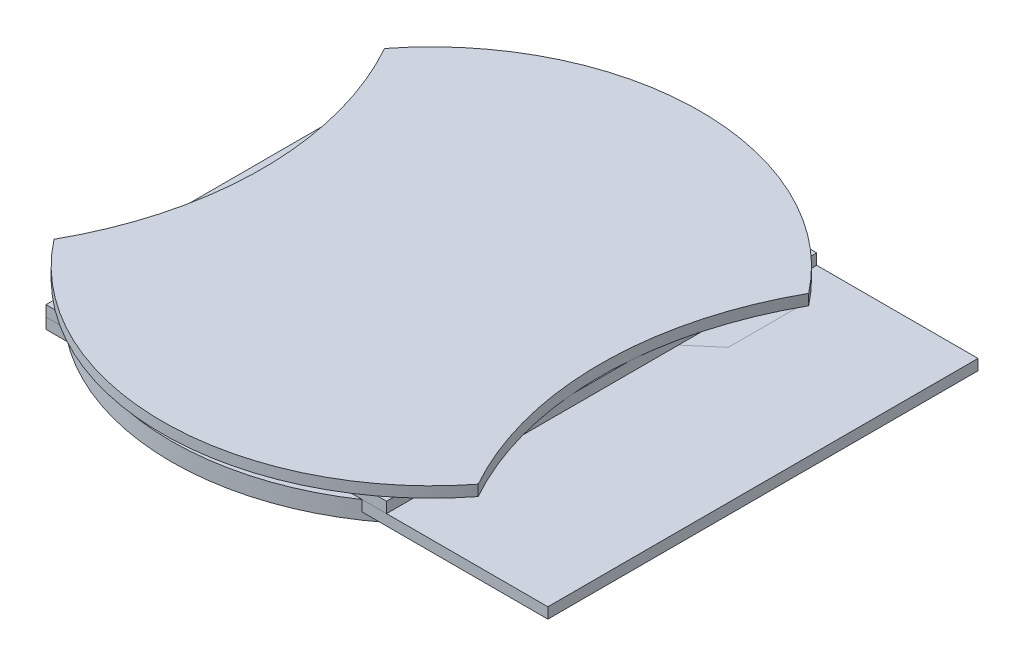
SolidWorks part; units mm, degrees
other "Markup1"
sketch "Sketch33" plane through (-11.66, 9, -138.7946) normal (0, 1, 0) x (1, 0, 0)
other "Markup2"
sketch "Sketch43" plane through (-27.5, 9, 15) normal (-0.0208, 0.9953, 0.0943) x (0.8809, -0.0263, 0.4725)
other "Markup3"
sketch "Sketch50" plane through (-27.5, -2, -135) normal (0, -1, 0) x (1, 0, 0)
material "PMMA"
ref_plane "Front Plane" through (0, 0, 0) normal (0, 0, 1) x (1, 0, 0)
ref_plane "Top Plane" through (0, 0, 0) normal (0, 1, 0) x (1, 0, 0)
ref_plane "Right Plane" through (0, 0, 0) normal (1, 0, 0) x (0, 0, -1)
sketch "Sketch1" plane through (0, 0, 0) normal (0, 1, 0) x (1, 0, 0)
  line L1 (0, 0) -> (140, 0)
  line L2 (0, 0) -> (0, 120)
  line L3 (0, 120) -> (140, 120)
  line L4 (140, 0) -> (140, 120)
  dimension "D1" = 120
  dimension "D2" = 140
extrude "Compact" add sketch "Sketch1" along normal blind 3
sketch "Center Guide" plane through (0, 0, 0) normal (-1, 0, 0) x (0, 0, 1)
  line L0 (-60, 0) -> (-60, -3) construction
  line L1 (-120, 0) -> (0, 0) construction
  line L2 (-60, 3) -> (-60, 16.3)
  line L3 (-120, 3) -> (0, 3) construction
  line L4 (-60, 3) -> (-60, 24.5)
  circle A0 centre (-60, -3) radius 10.0584
  circle A1 centre (-60, 16.3) radius 5.9898
  circle A2 centre (-60, 24.5) radius 8.3651
  dimension "D2" = 13.3
  dimension "D3" = 21.5
  dimension "D1" = 3
sketch "Sketch4" plane through (0, 3, 0) normal (0, 1, 0) x (1, 0, 0)
  line L0 (0, 0) -> (140, 0) construction
  line L1 (0, 120) -> (95, 120)
  line L2 (0, 120) -> (0, 0)
  line L3 (0, 0) -> (95, 0)
  line L4 (95, 120) -> (95, 0)
  dimension "D1" = 95
extrude "SuperCompact" add sketch "Sketch4" along normal blind 3 separate body
sketch "Sketch5" plane through (0, 6, 0) normal (0, 1, 0) x (1, 0, 0)
  line L0 (47.5, 120) -> (47.5, 103.0921) construction
  line L1 (95, 120) -> (0, 120) construction
  line L2 (0, 60) -> (21.8037, 60) construction
  line L3 (0, 120) -> (0, 0) construction
  line L4 (70, 120) -> (70, 93.0513) construction
  line L5 (140, 120) -> (0, 120) construction
  circle A0 centre (5, 115) radius 1.5
  circle A1 centre (90, 115) radius 1.5
  circle A2 centre (90, 5) radius 1.5
  circle A3 centre (5, 5) radius 1.5
  circle A4 centre (135, 5) radius 1.5
  circle A5 centre (135, 115) radius 1.5
  dimension "D1" = 3
  dimension "D2" = 5
  dimension "D3" = 5
sketch "Sketch7" plane through (0, 6, 0) normal (0, 1, 0) x (1, 0, 0)
  line L0 (47.5, 120) -> (47.5, 0) construction
  line L1 (95, 120) -> (0, 120) construction
  line L2 (0, 0) -> (95, 0) construction
  circle A0 centre (47.5, 60) radius 75
  dimension "D1" = 150
extrude "Apple Base" add sketch "Sketch7" along normal blind 3 separate body
sketch "Sketch8" plane through (0, 9, 0) normal (0, 1, 0) x (1, 0, 0)
  line L1 (0, 120) -> (0, 0) construction
  line L2 (0, 100.6202) -> (0, 77.7186) construction
  line L3 (47.5, 135) -> (47.5, 108.0988) construction
  line L7 (-27.5, 60) -> (-27.5, 91.6393) construction
  arc A1 (-11.66, 106.0987) -> (-11.66, 13.9013) centre (-94.1268, 60) cw
  circle A2 centre (47.5, 60) radius 75 construction
  circle A3 centre (47.5, 60) radius 75
  arc A4 (-11.66, 106.0987) -> (-11.66, 13.9013) centre (47.5, 60) ccw
  arc A5 (106.66, 106.0987) -> (106.66, 13.9013) centre (189.1268, 60) ccw
  arc A6 (106.66, 106.0987) -> (106.66, 13.9013) centre (47.5, 60) cw
  dimension "D2" = 0
extrude "SideCuts" cut sketch "Sketch8" against normal through all
sketch "Sketch9" plane through (0, 6, 0) normal (0, -1, 0) x (1, 0, 0)
  arc A4 (106.66, -13.9013) -> (-11.66, -13.9013) centre (47.5, -60) ccw
  arc A5 (-11.66, -106.0987) -> (-11.66, -13.9013) centre (-94.1268, -60) ccw
  arc A6 (-11.66, -106.0987) -> (106.66, -106.0987) centre (47.5, -60) ccw
  arc A7 (106.66, -13.9013) -> (106.66, -106.0987) centre (189.1268, -60) ccw
  arc A8 (106.66, -13.9013) -> (-11.66, -13.9013) centre (47.5, -60) ccw
  arc A9 (-11.66, -106.0987) -> (-11.66, -13.9013) centre (-94.1268, -60) ccw
  arc A10 (-11.66, -106.0987) -> (106.66, -106.0987) centre (47.5, -60) ccw
  arc A11 (106.66, -13.9013) -> (106.66, -106.0987) centre (189.1268, -60) ccw
  dimension "D1" = 0
extrude "Apple_Base" add sketch "Sketch9" along normal blind 3 separate body
sketch "Sketch10" plane through (0, 6, 0) normal (0, 1, 0) x (1, 0, 0)
  line L0 (-11.66, 106.0987) -> (-11.66, 13.9013)
  line L1 (106.66, 106.0987) -> (106.66, 13.9013)
  arc A4 (106.66, 106.0987) -> (106.66, 13.9013) centre (189.1268, 60) ccw
  arc A5 (106.66, 106.0987) -> (-11.66, 106.0987) centre (47.5, 60) ccw
  arc A6 (-11.66, 13.9013) -> (-11.66, 106.0987) centre (-94.1268, 60) ccw
  arc A7 (-11.66, 13.9013) -> (106.66, 13.9013) centre (47.5, 60) ccw
  arc A8 (106.66, 106.0987) -> (106.66, 13.9013) centre (189.1268, 60) ccw
  arc A10 (-11.66, 13.9013) -> (-11.66, 106.0987) centre (-94.1268, 60) ccw
  dimension "D1" = 0
extrude "Boss-Extrude4" add sketch "Sketch10" against normal blind 3
sketch "Sketch11" plane through (0, 0, 0) normal (0, 0, 1) x (1, 0, 0)
  line L0 (-11.66, 6) -> (106.66, 6)
  line L1 (47.5, 6) -> (47.5, 18.0317)
fillet "Base_Plate_Fillet" radius 0.001 12 edges at (106.66, 6, -60) (106.66, 3, -60) (-11.66, 6, -60) (-11.66, 3, -60) (47.5, 6, -135) (47.5, 3, -135) (47.5, 6, 15) (47.5, 3, 15) (106.66, 4.5, -106.0987) (-11.66, 4.5, -106.0987) (-11.66, 4.5, -13.9013) (106.66, 4.5, -13.9013)
sketch "Sketch12" plane through (0, 6, 0) normal (0, 1, 0) x (1, 0, 0)
  line L0 (-11.659, 106.0984) -> (-11.659, 13.9016) construction
  line L1 (106.659, 13.9016) -> (106.659, 106.0984) construction
  line L2 (-4.6496, 43.9016) -> (-4.6496, 76.9016) construction
  line L3 (47.5, 134.999) -> (47.5, 105.9694) construction
  circle A0 centre (-4.6496, 43.9016) radius 2.5
  circle A1 centre (-4.6496, 76.9016) radius 2.5
  arc A2 (106.659, 106.0984) -> (-11.659, 106.0984) centre (47.5, 60) ccw construction
  circle A6 centre (99.659, 75.8016) radius 2.5
  circle A7 centre (99.659, 42.8016) radius 2.5
  dimension "D3" = 5
  dimension "D5" = 5
  dimension "D1" = 30
  dimension "D2" = 7.0094
  dimension "D4" = 33
  dimension "D6" = 33
  dimension "D7" = 28.9
  dimension "D8" = 7
extrude "Base_Screw_Holes" [suppressed] cut sketch "Sketch12" against normal blind 14
ref_plane "MidPlane" through (0, 0, -60) normal (0, 0, 1) x (1, 0, 0)
sketch "Sketch24" plane through (0, 6, 0) normal (0, 1, 0) x (1, 0, 0)
  line L0 (-3.66, 114.8421) -> (-3.66, 5.1579)
  line L2 (-11.66, 13.9016) -> (-11.66, 106.0984) construction
  line L3 (47.5, 134.999) -> (47.5, 105.1076) construction
  line L4 (98.66, 114.8421) -> (98.66, 5.1579)
  line L5 (106.66, 106.0984) -> (106.66, 13.9016) construction
  line L6 (106.66, 106.0984) -> (106.66, 13.9016)
  line L7 (-11.66, 13.9016) -> (-11.66, 106.0984)
  arc A0 (106.659, 106.0984) -> (-11.659, 106.0984) centre (47.5, 60) ccw construction
  arc A1 (-11.6598, 106.099) -> (-11.66, 106.0984) centre (-11.659, 106.0984) ccw construction
  arc A2 (106.6598, 106.099) -> (-11.6598, 106.099) centre (47.5, 60) ccw construction
  arc A3 (106.66, 106.0984) -> (106.6598, 106.099) centre (106.659, 106.0984) ccw construction
  arc A4 (106.6598, 13.901) -> (106.66, 13.9016) centre (106.659, 13.9016) ccw construction
  arc A5 (-11.6598, 13.901) -> (106.6598, 13.901) centre (47.5, 60) ccw construction
  arc A6 (-11.66, 13.9016) -> (-11.6598, 13.901) centre (-11.659, 13.9016) ccw construction
  arc A7 (-11.6598, 106.099) -> (-11.66, 106.0984) centre (-11.659, 106.0984) ccw
  arc A8 (106.6598, 106.099) -> (98.66, 114.8421) centre (47.5, 60) ccw
  arc A9 (106.66, 106.0984) -> (106.6598, 106.099) centre (106.659, 106.0984) ccw
  arc A10 (106.6598, 13.901) -> (106.66, 13.9016) centre (106.659, 13.9016) ccw
  arc A11 (-11.6598, 13.901) -> (-3.66, 5.1579) centre (47.5, 60) ccw
  arc A12 (-11.66, 13.9016) -> (-11.6598, 13.901) centre (-11.659, 13.9016) ccw
  arc A13 (98.66, 5.1579) -> (106.6598, 13.901) centre (47.5, 60) ccw
  arc A14 (-3.66, 114.8421) -> (-11.6598, 106.099) centre (47.5, 60) ccw
  dimension "D1" = 8
  dimension "D2" = 8
extrude "Cut-Extrude3" [suppressed] cut sketch "Sketch24" against normal blind 6
sketch "Sketch25" plane through (0, 6, 0) normal (0, 1, 0) x (1, 0, 0)
  line L0 (-11.659, 106.0974) -> (-11.659, 111.0974)
  line L1 (47.5, 135) -> (47.5, 124.3332) construction
  line L2 (106.659, 106.0974) -> (106.659, 111.0974)
  line L3 (-11.66, 60) -> (55.4784, 60) construction
  line L4 (-11.66, 13.9016) -> (-11.66, 106.0984) construction
  line L5 (106.659, 13.9026) -> (106.659, 8.9026)
  line L6 (-11.659, 13.9026) -> (-11.659, 8.9026)
  arc A0 (-11.6598, 106.099) -> (-11.66, 106.0984) centre (-11.659, 106.0984) ccw construction
  arc A1 (106.6598, 106.099) -> (-11.6598, 106.099) centre (47.5, 60) ccw construction
  arc A2 (-11.659, 111.0974) -> (106.659, 111.0974) centre (47.5, 61.7666) cw
  arc A3 (-11.659, 106.0974) -> (106.659, 106.0974) centre (47.5, 56.7666) cw
  arc A4 (-11.659, 13.9026) -> (106.659, 13.9026) centre (47.5, 63.2334) ccw
  arc A5 (-11.659, 8.9026) -> (106.659, 8.9026) centre (47.5, 58.2334) ccw
  arc M15 (106.659, 106.0984) -> (-11.659, 106.0984) centre (47.5, 60) ccw
  arc M17 (-11.659, 13.9016) -> (106.659, 13.9016) centre (47.5, 60) ccw
  dimension "D1" = 5
extrude "Top Bottom extensions" add sketch "Sketch25" against normal blind 3 contours L6 A5 L5 A4 M17 | L0 A3 L2 A2 M15
sketch "Sketch28" plane through (0, 6, 0) normal (0, 1, 0) x (1, 0, 0)
  line L0 (-11.659, 60) -> (106.659, 60) construction
  line L1 (37.5, 6) -> (57.5, 6) construction
  line L2 (37.5, 6) -> (37.5, -14) construction
  line L3 (37.5, -14) -> (57.5, -14) construction
  line L4 (57.5, 6) -> (57.5, -14) construction
  line L5 (-11.659, 106.0984) -> (-11.659, 13.9016) construction
  line L6 (106.659, 13.9016) -> (106.659, 106.0984) construction
  line L7 (47.5, 6) -> (47.5, -4) construction
  line L8 (47.5, -4) -> (37.5, -4) construction
  circle A0 centre (41.5, 2) radius 1.75
  circle A1 centre (41.5, -10) radius 1.75
  circle A2 centre (53.5, -10) radius 1.75
  circle A3 centre (53.5, 2) radius 1.75
  circle A4 centre (53.5, 130) radius 1.75
  circle A5 centre (53.5, 118) radius 1.75
  circle A6 centre (41.5, 118) radius 1.75
  circle A7 centre (41.5, 130) radius 1.75
  point P30 (47.5, 60)
  dimension "D4" = 3.5
  dimension "D1" = 20
  dimension "D2" = 20
  dimension "D3" = 54
  dimension "D5" = 4
  dimension "D6" = 4
extrude "RodHolder holes" [suppressed] cut sketch "Sketch28" against normal blind 11
sketch "Sketch29" plane through (0, 6, 0) normal (0, 1, 0) x (1, 0, 0)
  line L0 (47.5, 138.7946) -> (47.5, -18.7946) construction
  line L5 (47.5, 60) -> (59.8359, 60) construction
  line L7 (11.25, 7.85) -> (83.75, 7.85) construction
  line L8 (11.25, 7.85) -> (11.25, 112.15) construction
  line L9 (11.25, 112.15) -> (83.75, 112.15) construction
  line L10 (83.75, 7.85) -> (83.75, 112.15) construction
  line L11 (11.25, 7.85) -> (83.75, 112.15) construction
  line L12 (11.25, 112.15) -> (83.75, 7.85) construction
  arc A5 (106.659, 111.0974) -> (-11.659, 111.0974) centre (47.5, 61.7666) ccw construction
  arc A6 (-11.659, 8.9026) -> (106.659, 8.9026) centre (47.5, 58.2334) ccw construction
  circle A7 centre (11.25, 112.15) radius 1.5
  circle A8 centre (83.75, 112.15) radius 1.5
  circle A9 centre (83.75, 7.85) radius 1.5
  circle A10 centre (11.25, 7.85) radius 1.5
  point P9 (47.5, 60)
  dimension "D1" = 104.3
  dimension "D3" = 3
  dimension "D2" = 72.5
extrude "Height extender holes" [suppressed] cut sketch "Sketch29" against normal blind 10
sketch "Sketch31" plane through (0, 6, 0) normal (0, 1, 0) x (1, 0, 0)
  line L0 (-11.659, 60) -> (106.659, 60) construction
  line L1 (-11.659, 106.0984) -> (-11.659, 13.9016) construction
  line L2 (106.659, 13.9016) -> (106.659, 106.0984) construction
  line L3 (47.5, 138.7946) -> (47.5, -18.7946) construction
  line L4 (47.5, 112) -> (72.8768, 112) construction
  arc A0 (106.659, 111.0974) -> (-11.659, 111.0974) centre (47.5, 61.7666) ccw construction
  arc A1 (-11.659, 8.9026) -> (106.659, 8.9026) centre (47.5, 58.2334) ccw construction
  circle A2 centre (47.5, 122) radius 10
  circle A3 centre (47.5, 122) radius 8
  circle A4 centre (47.5, 122) radius 15
  dimension "D1" = 20
  dimension "D3" = 2
  dimension "D4" = 30
  dimension "D2" = 52
sketch "Sketch34" plane through (0, 3, 0) normal (0, -1, 0) x (-1, 0, 0)
  line L0 (-47.5, -18.7946) -> (-47.5, 138.7946) construction
  arc A0 (-106.659, 8.9026) -> (11.659, 8.9026) centre (-47.5, 58.2334) ccw construction
  arc A1 (11.659, 111.0974) -> (-106.659, 111.0974) centre (-47.5, 61.7666) ccw construction
  circle A2 centre (-47.5, 60) radius 12.859
sketch "Sketch35" plane through (0, 3, 0) normal (0, -1, 0) x (1, 0, 0)
  line L0 (47.5, 18.7946) -> (47.5, -138.7946) construction
  line L1 (6.25, -114.85) -> (88.75, -114.85) construction
  line L2 (47.5, -60) -> (61.5955, -60) construction
  line L3 (7.5, -3.9) -> (7.5, -116.1) construction
  line L4 (6.25, -5.15) -> (86.25, -5.15) construction
  line L5 (87.5, -3.9) -> (87.5, -116.1) construction
  line L6 (7.5, 18.7946) -> (7.5, -138.7946) construction
  line L7 (87.5, 18.7946) -> (87.5, -138.7946) construction
  arc A0 (106.659, -8.9026) -> (-11.659, -8.9026) centre (47.5, -58.2334) ccw construction
  arc A1 (-11.659, -111.0974) -> (106.659, -111.0974) centre (47.5, -61.7666) ccw construction
  circle A2 centre (7.5, -5.15) radius 1.25
  circle A3 centre (87.5, -5.15) radius 1.25
  circle A4 centre (87.5, -114.85) radius 1.25
  circle A5 centre (7.5, -114.85) radius 1.25
  dimension "D1" = 40
  dimension "D3" = 2.5
  dimension "D4" = 80
  dimension "D5" = 112.2
  dimension "D2" = 40
extrude "SpacerHoles" cut sketch "Sketch35" against normal blind 10
sketch "Sketch37" plane through (0, 3, 0) normal (0, -1, 0) x (1, 0, 0)
sketch "Sketch38" plane through (0, 3, 0) normal (0, -1, 0) x (1, 0, 0)
  line L0 (-11.659, -60) -> (-6.659, -60)
  line L1 (-11.659, -13.9016) -> (-11.659, -106.0984) construction
  line L2 (-6.659, -60) -> (-6.659, 24.7024)
  line L3 (101.659, -60) -> (106.659, -60)
  line L4 (106.659, -106.0984) -> (106.659, -13.9016) construction
  line L5 (-6.659, 24.7024) -> (101.659, 24.7024)
  line L6 (101.659, 24.7024) -> (101.659, -143.8435)
  line L7 (101.659, -143.8435) -> (-6.659, -143.8435)
  line L8 (-6.659, -143.8435) -> (-6.659, -60)
  line L9 (47.5, 37.0501) -> (120.3723, 37.0501)
  line L10 (120.3723, 37.0501) -> (120.3723, -158.6018)
  line L11 (120.3723, -158.6018) -> (-29.1775, -158.6018)
  line L12 (-29.1775, -158.6018) -> (-29.1775, 37.0501)
  line L13 (-29.1775, 37.0501) -> (47.5, 37.0501)
  line M7 (106.659, -106.0984) -> (106.659, -13.9016)
  line M8 (106.659, -13.9016) -> (106.659, -8.9026)
  arc M9 (106.659, -8.9026) -> (-11.659, -8.9026) centre (47.5, -58.2334) ccw
  line M10 (-11.659, -8.9026) -> (-11.659, -13.9016)
  line M11 (-11.659, -13.9016) -> (-11.659, -106.0984)
  line M12 (-11.659, -106.0984) -> (-11.659, -111.0974)
  arc M13 (-11.659, -111.0974) -> (106.659, -111.0974) centre (47.5, -61.7666) ccw
  line M14 (106.659, -111.0974) -> (106.659, -106.0984)
  dimension "D1" = 5
  dimension "D2" = 5
extrude "Cut-Extrude4" cut sketch "Sketch38" against normal blind 10 contours L13 L12 L11 L10 L9 L7 L8 L2 L5 L6 M13 M12 M11 M10 M9 M8 M7 M14 | L6 L3 M9 M7 M8 | L0 L2 M9 M10 M11 | L8 L0 M13 M11 M12 | L3 L6 M13 M14 M7
sketch "Sketch39" plane through (0, 3, 0) normal (0, -1, 0) x (1, 0, 0)
  line L0 (47.5, 18.7946) -> (47.5, -81.8228) construction
  line L2 (101.659, -60) -> (38.5892, -60) construction
  line L3 (101.659, -3.4601) -> (101.659, -116.5399) construction
  arc A1 (101.659, -3.4601) -> (-6.659, -3.4601) centre (47.5, -58.2334) ccw construction
  circle A2 centre (47.5, -60) radius 72.5
  circle A3 centre (87.5, -5.15) radius 1.25
  circle A4 centre (7.5, -5.15) radius 1.25
  circle A5 centre (7.5, -114.85) radius 1.25
  circle A6 centre (87.5, -114.85) radius 1.25
  dimension "D1" = 145
extrude "Boss-Extrude5" add sketch "Sketch39" along normal blind 5
sketch "Sketch40" plane through (101.659, 0, 0) normal (1, 0, 0) x (0, 0, -1)
  line L0 (3.4601, 3) -> (-22.7338, 3)
  line L1 (-22.7338, 3) -> (-22.7338, 8.214)
  line L2 (-22.7338, 8.214) -> (147.503, 8.214)
  line L3 (147.503, 8.214) -> (147.503, 3)
  line L4 (147.503, 3) -> (3.4601, 3)
extrude "Cut-Extrude5" cut sketch "Sketch40" against normal blind 150
sketch "Sketch41" plane through (0, 3, 0) normal (0, 1, 0) x (1, 0, 0)
  line L0 (47.5, 60) -> (97.5, 60)
  circle A3 centre (47.5, 60) radius 8.4
  circle A4 centre (97.5, 60) radius 8.5
  dimension "D2" = 50
  dimension "D6" = 16.8
  dimension "D4" = 17
extrude "Cut-Extrude6" cut sketch "Sketch41" against normal blind 10
sketch "Sketch45" plane through (0, -2, 0) normal (0, -1, 0) x (1, 0, 0)
  line L0 (47.5, -60) -> (47.5, -41.4206) construction
  line L1 (47.5, -60) -> (76.9611, -19.6014)
  line L2 (47.5, -60) -> (69.1497, -60) construction
  circle A0 centre (76.9611, -19.6014) radius 3.5
  circle A1 centre (18.0389, -19.6014) radius 3.5
  circle A2 centre (76.9611, -100.3986) radius 3.5
  circle A3 centre (18.0389, -100.3986) radius 3.5
  dimension "D2" = 7
  dimension "D1" = 50
  dimension "D3" = 40.3986
  dimension "D4" = 29.4611
  dimension "D5" = 50
  dimension "D6" = 40.3986
  dimension "D7" = 29.4611
  dimension "D8" = 50
  dimension "D9" = 29.4611
extrude "Cut-Extrude8" cut sketch "Sketch45" against normal blind 12 contours A2 | A3 | A1
sketch "Sketch46" plane through (0, -2, 0) normal (0, -1, 0) x (1, 0, 0)
  line L0 (18.0389, -19.6014) -> (18.0389, -100.3986) construction
  line L1 (47.5, -60) -> (47.5, -35.46) construction
  line L2 (76.9611, -19.6014) -> (76.9611, -100.3986) construction
  circle A0 centre (76.9611, -19.6014) radius 3.5
  circle A1 centre (18.0389, -19.6014) radius 3.5 construction
extrude "Cut-Extrude9" cut sketch "Sketch46" against normal blind 10
sketch "Sketch47" plane through (0, -2, 0) normal (0, -1, 0) x (1, 0, 0)
  circle A0 centre (7.5, -5.15) radius 3.3212
  circle A1 centre (87.5, -5.15) radius 3.0237
  circle A2 centre (87.5, -114.85) radius 2.8026
  circle A3 centre (7.5, -114.85) radius 2.4866
extrude "Boss-Extrude6" add sketch "Sketch47" against normal blind 5
sketch "Sketch48" plane through (0, -2, 0) normal (0, -1, 0) x (1, 0, 0)
  circle A0 centre (47.5, -60) radius 12.0797
extrude "Boss-Extrude7" add sketch "Sketch48" against normal blind 5
sketch "Sketch49" plane through (0, -2, 0) normal (0, -1, 0) x (1, 0, 0)
  line L1 (47.5, -52.75) -> (41.2213, -56.375)
  line L2 (41.2213, -56.375) -> (41.2213, -63.625)
  line L3 (41.2213, -63.625) -> (47.5, -67.25)
  line L4 (47.5, -67.25) -> (53.7787, -63.625)
  line L5 (53.7787, -63.625) -> (53.7787, -56.375)
  line L6 (53.7787, -56.375) -> (47.5, -52.75)
  circle A0 centre (47.5, -60) radius 6.2787 construction
  dimension "D1" = 14.5
extrude "Cut-Extrude10" cut sketch "Sketch49" against normal blind 5
sketch "Sketch51" plane through (0, -2, 0) normal (0, -1, 0) x (1, 0, 0)
  line L0 (47.5, -60) -> (102.5, -60)
  line L1 (47.5, -60) -> (-7.5, -60)
  line L2 (102.5, -60) -> (102.5, -4.0451)
  line L3 (-7.5, -60) -> (-7.5, -4.0451)
  line L4 (-7.5, -4.0451) -> (-39.3853, -4.0451)
  line L5 (-39.3853, -4.0451) -> (-39.3853, -125.5644)
  line L6 (-39.3853, -125.5644) -> (-7.5, -125.5644)
  line L7 (-7.5, -125.5644) -> (-7.5, -60)
  line L8 (102.5, -4.0451) -> (138.5894, -4.0451)
  line L9 (138.5894, -4.0451) -> (138.5894, -125.5644)
  line L10 (138.5894, -125.5644) -> (102.5, -125.5644)
  line L11 (102.5, -125.5644) -> (102.5, -60)
  circle M12 centre (47.5, -60) radius 72.5
  dimension "D1" = 55
  dimension "D2" = 55
extrude "Cut-Extrude11" cut sketch "Sketch51" against normal blind 10 contours L7 L3 M12 | L11 L2 M12
sketch "Sketch52" plane through (0, -2, 0) normal (0, -1, 0) x (1, 0, 0)
  line L1 (53.7787, -56.375) -> (47.5, -52.75)
  line L2 (47.5, -52.75) -> (41.2213, -56.375)
  line L3 (41.2213, -56.375) -> (41.2213, -63.625)
  line L4 (41.2213, -63.625) -> (47.5, -67.25)
  line L5 (47.5, -67.25) -> (53.7787, -63.625)
  line L6 (53.7787, -63.625) -> (53.7787, -56.375)
  circle A0 centre (47.5, -60) radius 6.2787 construction
  circle A1 centre (47.5, -60) radius 3.9
  dimension "D1" = 7.8
extrude "Boss-Extrude9" add sketch "Sketch52" along normal blind 1 and the other way blind 5 separate body
chamfer "Chamfer1" distance 1 angle 45 1 edges at (47.5, -3, -63.9)
cosmetic thread "Cosmetic Thread1" parameters "D1"=5, "D2"=10
chamfer "Chamfer2" distance 1 angle 45 1 edges at (47.5, 3, -63.9)
